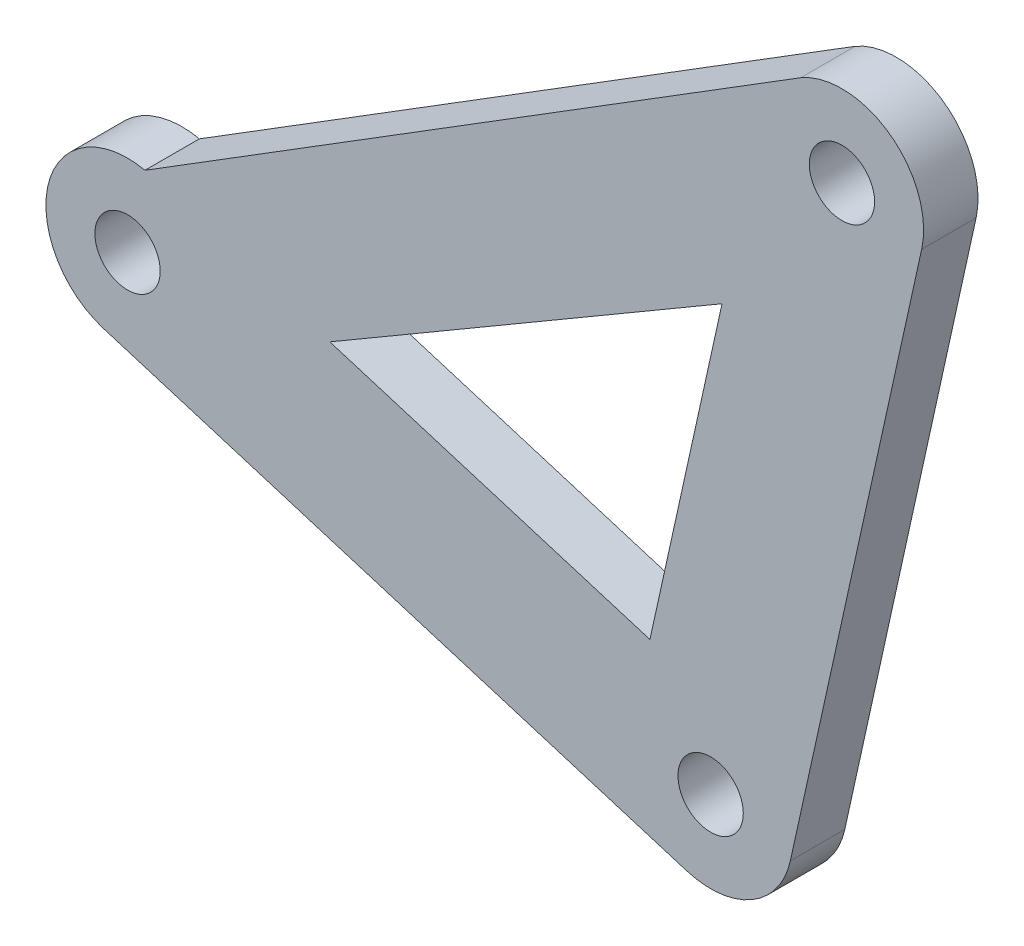
SolidWorks part; units mm, degrees
ref_plane "Plan de face" through (0, 0, 0) normal (0, 0, 1) x (1, 0, 0)
ref_plane "Plan de dessus" through (0, 0, 0) normal (0, 1, 0) x (1, 0, 0)
ref_plane "Plan de droite" through (0, 0, 0) normal (1, 0, 0) x (0, 0, -1)
sketch "Esquisse1" plane through (0, 0, 0) normal (0, 0, 1) x (1, 0, 0)
  line L0 (-117.5602, 12.3494) -> (-64, -4) construction
  line L1 (-115.3706, 19.5227) -> (-61.8103, 3.1732)
  line L2 (-119.7499, 5.1762) -> (-66.1897, -11.1732)
  line L3 (-64, -4) -> (-51.9374, 50.6854) construction
  line L4 (-71.3239, -2.3845) -> (-59.2613, 52.3009)
  line L5 (-56.6761, -5.6155) -> (-44.6135, 49.0699)
  line L6 (-51.9374, 50.6854) -> (-117.5602, 12.3494) construction
  line L7 (-48.1542, 44.2095) -> (-113.7771, 5.8735)
  line L8 (-55.7206, 57.1613) -> (-121.3434, 18.8254)
  line L9 (-98.9781, 14.5188) -> (-62.9532, 35.5641)
  line L10 (-62.9532, 35.5641) -> (-69.5752, 5.5435)
  line L11 (-69.5752, 5.5435) -> (-98.9781, 14.5188)
  line L12 (-119.7499, 5.1762) -> (-66.1897, -11.1732)
  line L13 (-44.6135, 49.0699) -> (-56.6761, -5.6155)
  line L14 (-55.7206, 57.1613) -> (-122.5274, 15.591)
  arc A0 (-115.3706, 19.5227) -> (-119.7499, 5.1762) centre (-117.5602, 12.3494) ccw
  arc A1 (-66.1897, -11.1732) -> (-61.8103, 3.1732) centre (-64, -4) ccw
  arc A2 (-71.3239, -2.3845) -> (-56.6761, -5.6155) centre (-64, -4) ccw
  arc A3 (-44.6135, 49.0699) -> (-59.2613, 52.3009) centre (-51.9374, 50.6854) ccw
  arc A4 (-48.1542, 44.2095) -> (-55.7206, 57.1613) centre (-51.9374, 50.6854) ccw
  arc A5 (-121.3434, 18.8254) -> (-113.7771, 5.8735) centre (-117.5602, 12.3494) ccw
  point P4 (-90.7801, 4.1747)
  point P9 (-57.9687, 23.3427)
  point P17 (-84.7488, 31.5174)
  point P24 (-62.9532, 35.5641)
  point P25 (-69.5752, 5.5435)
  point P26 (-98.9781, 14.5188)
  dimension "D1" = 15
  dimension "D2" = 15
  dimension "D3" = 15
extrude "Boss.-Extru.1" add sketch "Esquisse1" against normal blind 5 contours A3 L8 A0 L1 L7 L4 | L7 A4 A3 L4 | A4 L7 L4 L1 A1 L5 | L4 A2 A1 L1 | A5 L2 A2 L4 L1 L7 | A0 A5 L7 L1
sketch "Esquisse2" plane through (0, 0, 0) normal (0, 0, 1) x (1, 0, 0)
  circle A0 centre (-117.5602, 12.3494) radius 3
  circle A1 centre (-64, -4) radius 3
  circle A2 centre (-51.9374, 50.6854) radius 3
  dimension "D1" = 6
  dimension "D2" = 6
  dimension "D3" = 6
extrude "Enlèv. mat.-Extru.1" cut sketch "Esquisse2" against normal through all both contours A0 | A1 | A2
